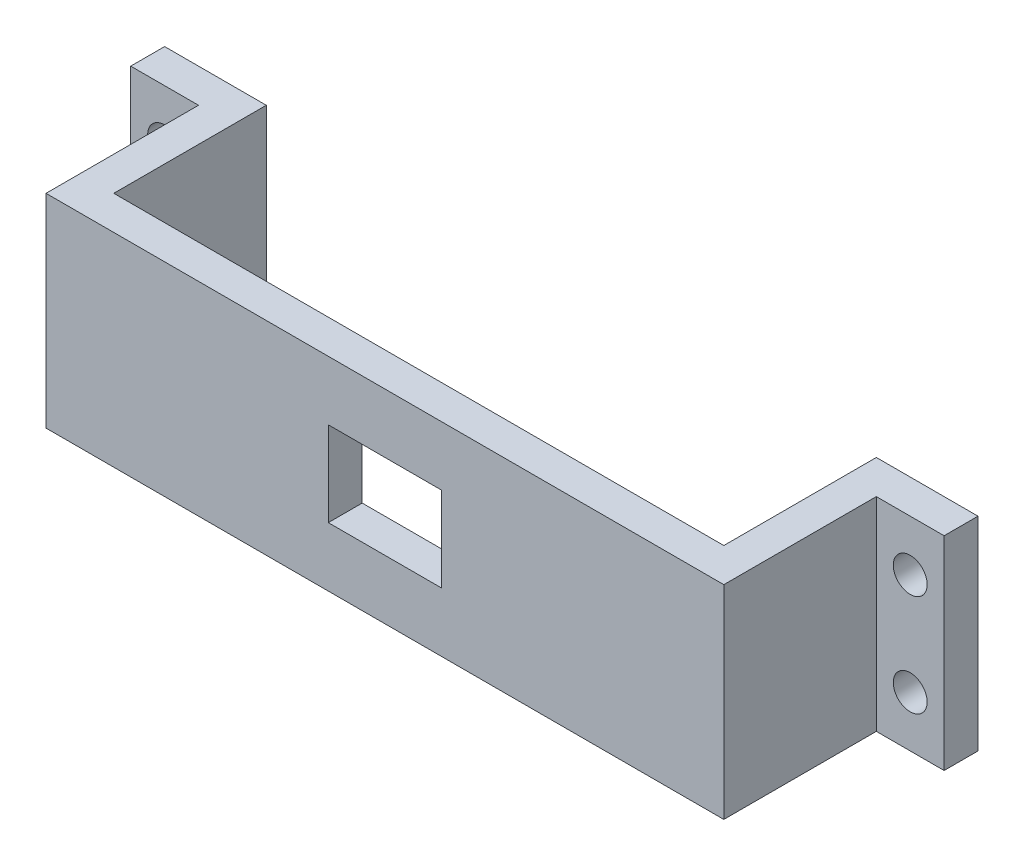
SolidWorks part; units mm, degrees
ref_plane "Front Plane" through (0, 0, 0) normal (0, 0, 1) x (1, 0, 0)
ref_plane "Top Plane" through (0, 0, 0) normal (0, 1, 0) x (1, 0, 0)
ref_plane "Right Plane" through (0, 0, 0) normal (1, 0, 0) x (0, 0, -1)
sketch "Sketch1" plane through (0, 0, 0) normal (0, 0, 1) x (1, 0, 0)
  line L0 (52.8955, 11.11) -> (0, 0) construction
  line L1 (0, 0) -> (127, 0)
  line L2 (0, 0) -> (0, 38.1)
  line L3 (0, 38.1) -> (127, 38.1)
  line L4 (127, 0) -> (127, 38.1)
  line L5 (52.8955, 11.11) -> (74.1045, 11.11)
  line L6 (52.8955, 11.11) -> (52.8955, 26.99)
  line L7 (52.8955, 26.99) -> (74.1045, 26.99)
  line L8 (74.1045, 11.11) -> (74.1045, 26.99)
  line L9 (74.1045, 11.11) -> (127, 0) construction
  line L10 (52.8955, 26.99) -> (0, 38.1) construction
  dimension "D1" = 127
  dimension "D2" = 38.1
  dimension "D3" = 15.8801
  dimension "D4" = 21.209
extrude "Boss-Extrude1" add sketch "Sketch1" along normal blind 6.35
sketch "Sketch2" plane through (0, 0, 0) normal (0, 0, -1) x (-1, 0, 0)
  line L0 (-127, 38.1) -> (0, 38.1) construction
  line L1 (0, 0) -> (-6.35, 0)
  line L2 (0, 0) -> (0, 38.1)
  line L3 (0, 38.1) -> (-6.35, 38.1)
  line L4 (-6.35, 0) -> (-6.35, 38.1)
  line L6 (-127, 0) -> (-120.65, 0)
  line L7 (-127, 0) -> (-127, 38.1)
  line L8 (-127, 38.1) -> (-120.65, 38.1)
  line L9 (-120.65, 0) -> (-120.65, 38.1)
  dimension "D1" = 6.35
extrude "Boss-Extrude2" add sketch "Sketch2" along normal blind 28.575
sketch "Sketch3" plane through (127, 0, 0) normal (1, 0, 0) x (0, 0, -1)
  line L0 (-6.35, 38.1) -> (28.575, 38.1) construction
  line L1 (28.575, 0) -> (22.225, 0)
  line L2 (28.575, 0) -> (28.575, 38.1)
  line L3 (28.575, 38.1) -> (22.225, 38.1)
  line L4 (22.225, 0) -> (22.225, 38.1)
  dimension "D1" = 6.35
extrude "Boss-Extrude3" add sketch "Sketch3" along normal blind 12.7
sketch "Sketch4" plane through (0, 0, 0) normal (-1, 0, 0) x (0, 0, 1)
  line L0 (6.35, 0) -> (-28.575, 0) construction
  line L1 (-28.575, 38.1) -> (-22.225, 38.1)
  line L2 (-28.575, 38.1) -> (-28.575, 0)
  line L3 (-28.575, 0) -> (-22.225, 0)
  line L4 (-22.225, 38.1) -> (-22.225, 0)
  dimension "D1" = 6.35
extrude "Boss-Extrude4" add sketch "Sketch4" along normal blind 12.7
sketch "Sketch5" plane through (0, 0, -22.225) normal (0, 0, 1) x (1, 0, 0)
  line L0 (133.35, 28.575) -> (133.35, 9.525) construction
  line L1 (133.35, 28.575) -> (139.7, 38.1) construction
  line L2 (133.35, 28.575) -> (127, 38.1) construction
  line L3 (-6.35, 28.575) -> (-6.35, 9.525) construction
  line L4 (-6.35, 9.525) -> (-12.7, 0) construction
  line L5 (-6.35, 9.525) -> (0, 0) construction
  line L6 (-12.7, 0) -> (0, 0) construction
  circle A0 centre (133.35, 28.575) radius 3.175
  circle A1 centre (133.35, 9.525) radius 3.175
  circle A2 centre (-6.35, 28.575) radius 3.175
  circle A3 centre (-6.35, 9.525) radius 3.175
  dimension "D1" = 6.35
  dimension "D2" = 6.35
  dimension "D5" = 6.35
  dimension "D6" = 6.35
  dimension "D3" = 19.05
  dimension "D4" = 9.525
  dimension "D7" = 19.05
  dimension "D8" = 9.525
extrude "Cut-Extrude1" cut sketch "Sketch5" against normal up to next
